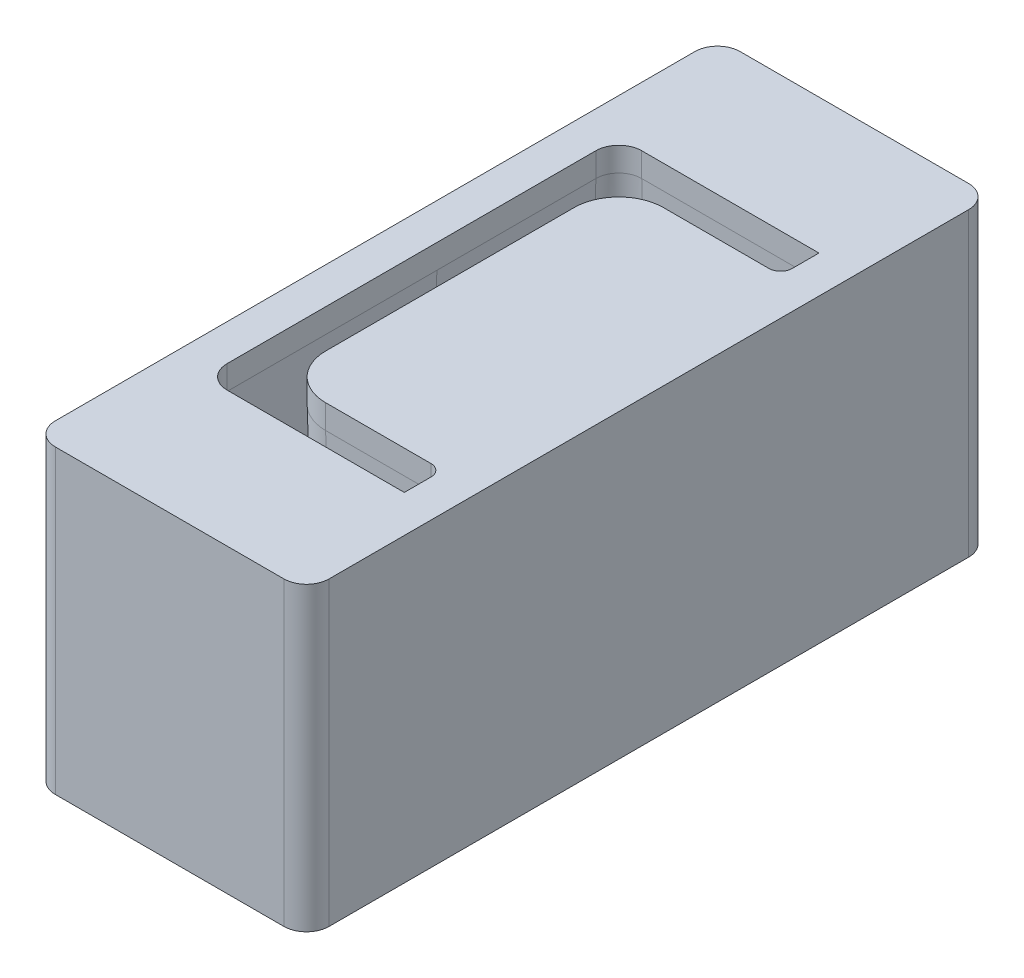
SolidWorks part; units mm, degrees
material "K110"
ref_plane "Front Plane" through (0, 0, 0) normal (0, 0, 1) x (1, 0, 0)
ref_plane "Top Plane" through (0, 0, 0) normal (0, 1, 0) x (1, 0, 0)
ref_plane "Right Plane" through (0, 0, 0) normal (1, 0, 0) x (0, 0, -1)
sketch "Sketch1" plane through (0, 0, 0) normal (0, 1, 0) x (1, 0, 0)
  line L1 (-3, -48.87) -> (33.38, -48.87)
  line L2 (-3, -48.87) -> (-3, 42.13)
  line L3 (-3, 42.13) -> (33.38, 42.13)
  line L4 (33.38, -48.87) -> (33.38, 42.13)
  line L5 (15.19, 42.13) -> (15.19, -48.87) construction
  line L6 (30.38, 42.13) -> (0, 42.13) construction
  line L8 (0, -48.87) -> (30.38, -48.87) construction
  line L9 (33.38, -3.37) -> (-3, -3.37) construction
  line L10 (33.38, -45.87) -> (33.38, 39.13) construction
  line L11 (-3, 39.13) -> (-3, -45.87) construction
  point P0 (0, 0)
extrude "Boss-Extrude1" add sketch "Sketch1" against normal blind 40
fillet "Fillet1" radius 3 4 edges at (-3, -20, -42.13) (33.38, -20, -42.13) (33.38, -20, 48.87) (-3, -20, 48.87)
sketch "Sketch2" plane through (0, 0, 0) normal (0, 1, 0) x (1, 0, 0)
  line L46 (28.43, 24.18) -> (4.88, 24.18)
  line L47 (28.43, 20.63) -> (28.43, 24.18)
  line L48 (12.88, 19.08) -> (26.88, 19.08)
  line L49 (6.93, -19.87) -> (6.93, 13.13)
  line L60 (26.88, -25.82) -> (12.88, -25.82)
  line L61 (28.43, -30.92) -> (28.43, -27.37)
  line L62 (4.88, -30.92) -> (28.43, -30.92)
  line L63 (1.83, 21.13) -> (1.83, -27.87)
  line L64 (28.43, 24.18) -> (4.88, 24.18)
  line L65 (28.43, 20.63) -> (28.43, 24.18)
  line L66 (12.88, 19.08) -> (26.88, 19.08)
  line L67 (6.93, -19.87) -> (6.93, 13.13)
  line L68 (26.88, -25.82) -> (12.88, -25.82)
  line L69 (28.43, -30.92) -> (28.43, -27.37)
  line L70 (4.88, -30.92) -> (28.43, -30.92)
  line L71 (1.83, 21.13) -> (1.83, -27.87)
  arc A36 (4.88, 24.18) -> (1.83, 21.13) centre (4.88, 21.13) ccw
  arc A37 (26.88, 19.08) -> (28.43, 20.63) centre (26.88, 20.63) ccw
  arc A38 (12.88, 19.08) -> (6.93, 13.13) centre (12.88, 13.13) ccw
  arc A39 (6.93, -19.87) -> (12.88, -25.82) centre (12.88, -19.87) ccw
  arc A40 (28.43, -27.37) -> (26.88, -25.82) centre (26.88, -27.37) ccw
  arc A41 (1.83, -27.87) -> (4.88, -30.92) centre (4.88, -27.87) ccw
  arc A42 (4.88, 24.18) -> (1.83, 21.13) centre (4.88, 21.13) ccw
  arc A43 (26.88, 19.08) -> (28.43, 20.63) centre (26.88, 20.63) ccw
  arc A44 (12.88, 19.08) -> (6.93, 13.13) centre (12.88, 13.13) ccw
  arc A45 (6.93, -19.87) -> (12.88, -25.82) centre (12.88, -19.87) ccw
  arc A46 (28.43, -27.37) -> (26.88, -25.82) centre (26.88, -27.37) ccw
  arc A47 (1.83, -27.87) -> (4.88, -30.92) centre (4.88, -27.87) ccw
  dimension "D1" = 0.05
extrude "Cut-Extrude1" cut sketch "Sketch2" against normal up to next
sketch "Sketch3" plane through (0, 0, 0) normal (0, 0, 1) x (1, 0, 0)
  line L0 (1.83, -3.2) -> (1.1877, -40)
  line L2 (0, -40) -> (30.38, -40) construction
  line L3 (1.1877, -40) -> (1.83, -40)
  line L4 (1.83, -40) -> (1.83, -3.2)
  line L5 (20.009, 0) -> (-20.009, 0) construction
  line L7 (1.83, -40) -> (1.83, 0) construction
  dimension "D1" = 1
  dimension "D2" = 3.2
sketch "Sketch4" plane through (0, 0, 0) normal (0, 1, 0) x (1, 0, 0)
  line L16 (28.43, 20.63) -> (28.43, 24.18) construction
  line L17 (28.43, -30.92) -> (28.43, -27.37) construction
  line L18 (26.88, -25.82) -> (12.88, -25.82) construction
  line L19 (6.93, -19.87) -> (6.93, 13.13) construction
  line L20 (12.88, 19.08) -> (26.88, 19.08) construction
  line L21 (4.88, -30.92) -> (28.43, -30.92) construction
  line L22 (1.83, 21.13) -> (1.83, -27.87) construction
  line L23 (28.43, 24.18) -> (4.88, 24.18) construction
  line L24 (28.43, 20.63) -> (28.43, 24.18)
  line L25 (28.43, -30.92) -> (28.43, -27.37)
  line L26 (26.88, -25.82) -> (12.88, -25.82)
  line L27 (6.93, -19.87) -> (6.93, 13.13)
  line L28 (12.88, 19.08) -> (26.88, 19.08)
  line L29 (4.88, -30.92) -> (28.43, -30.92)
  line L30 (1.83, 21.13) -> (1.83, -27.87)
  line L31 (28.43, 24.18) -> (4.88, 24.18)
  arc A12 (26.88, 19.08) -> (28.43, 20.63) centre (26.88, 20.63) ccw construction
  arc A13 (28.43, -27.37) -> (26.88, -25.82) centre (26.88, -27.37) ccw construction
  arc A14 (6.93, -19.87) -> (12.88, -25.82) centre (12.88, -19.87) ccw construction
  arc A15 (12.88, 19.08) -> (6.93, 13.13) centre (12.88, 13.13) ccw construction
  arc A16 (1.83, -27.87) -> (4.88, -30.92) centre (4.88, -27.87) ccw construction
  arc A17 (4.88, 24.18) -> (1.83, 21.13) centre (4.88, 21.13) ccw construction
  arc A18 (26.88, 19.08) -> (28.43, 20.63) centre (26.88, 20.63) ccw
  arc A19 (28.43, -27.37) -> (26.88, -25.82) centre (26.88, -27.37) ccw
  arc A20 (6.93, -19.87) -> (12.88, -25.82) centre (12.88, -19.87) ccw
  arc A21 (12.88, 19.08) -> (6.93, 13.13) centre (12.88, 13.13) ccw
  arc A22 (1.83, -27.87) -> (4.88, -30.92) centre (4.88, -27.87) ccw
  arc A23 (4.88, 24.18) -> (1.83, 21.13) centre (4.88, 21.13) ccw
sweep "Cut-Sweep1" cut profiles "Sketch3" path "Sketch4"
hole_wizard "M8 Tapped Hole1" positions "Sketch7" profile "Sketch6" tap size "M8" standard "ISO"
sketch "Sketch7" plane through (0, -40, 0) normal (0, -1, 0) x (-1, 0, 0)
  line L0 (-15.19, 42.13) -> (-15.19, 24.8223) construction
  line L1 (-30.38, 42.13) -> (0, 42.13) construction
  line L4 (-15.19, -48.87) -> (-15.19, -31.5623) construction
  line L5 (0, -48.87) -> (-30.38, -48.87) construction
  line L8 (-4.88, 24.8223) -> (-29.0723, 24.8223) construction
  line L9 (-29.0723, -31.5623) -> (-4.88, -31.5623) construction
  point P0 (-15.19, 33.4762)
  point P2 (-15.19, -40.2162)
sketch "Sketch6" plane through (15.19, -40, -33.4762) normal (1, 0, 0) x (0, 0, -1)
  line L0 (0, 0) -> (0, 24.2929)
  line L1 (0, 24.2929) -> (3.4, 22.25)
  line L2 (3.4, 22.25) -> (3.4, 0)
  line L5 (3.4, 0) -> (0, 0)
  line L10 (0, 24.2929) -> (-3.4, 22.25) construction
  line L11 (0, -6.35) -> (0, 107.95) construction
  dimension "Tap Drill Dia." = 6.8
  dimension "Tap Drill Depth" = 22.25
  dimension "Drill Angle" = 118
cosmetic thread "Hole Thread1"
cosmetic thread "Hole Thread2"
